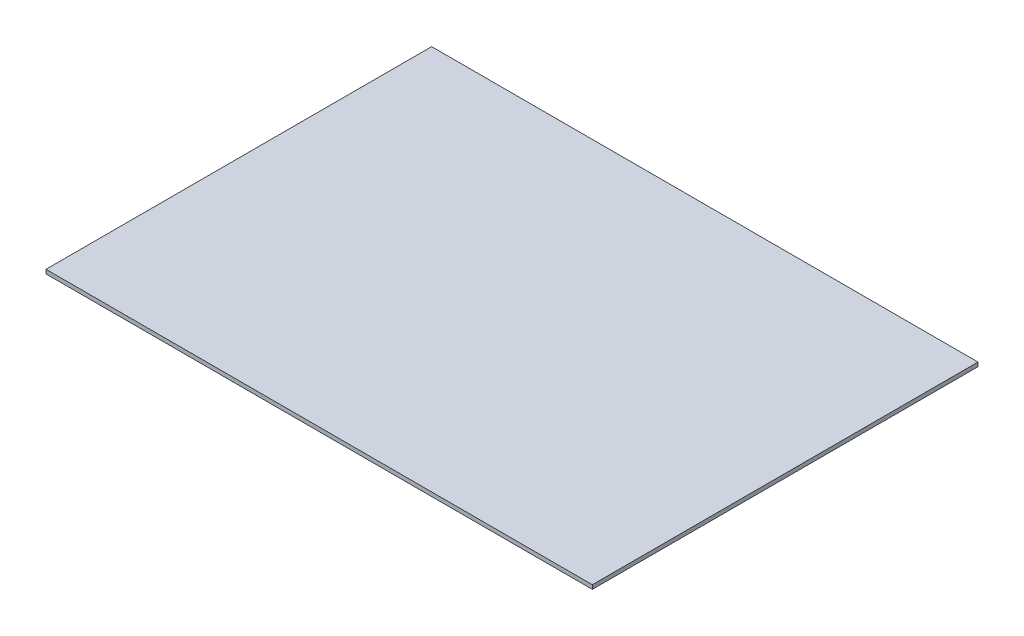
SolidWorks part; units mm, degrees
ref_plane "Front Plane" through (0, 0, 0) normal (0, 0, 1) x (1, 0, 0)
ref_plane "Top Plane" through (0, 0, 0) normal (0, 1, 0) x (1, 0, 0)
ref_plane "Right Plane" through (0, 0, 0) normal (1, 0, 0) x (0, 0, -1)
sketch "Sketch1" plane through (0, 0, 0) normal (0, 1, 0) x (1, 0, 0)
  line L1 (-57.4203, 242.861) -> (374.3797, 242.861)
  line L2 (-57.4203, 242.861) -> (-57.4203, -61.939)
  line L3 (-57.4203, -61.939) -> (374.3797, -61.939)
  line L4 (374.3797, 242.861) -> (374.3797, -61.939)
extrude "Boss-Extrude1" add sketch "Sketch1" along normal blind 3.175
